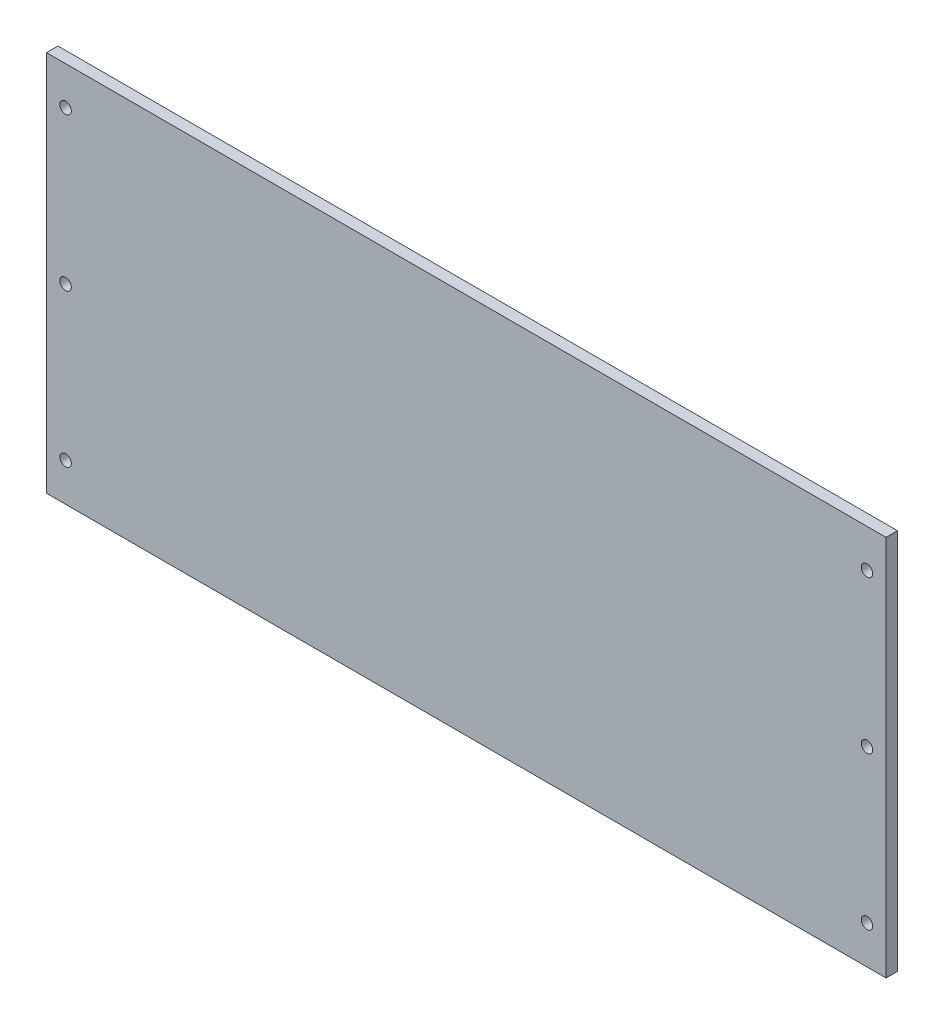
SolidWorks part; units mm, degrees
ref_plane "Plan de face" through (0, 0, 0) normal (0, 0, 1) x (1, 0, 0)
ref_plane "Plan de dessus" through (0, 0, 0) normal (0, 1, 0) x (1, 0, 0)
ref_plane "Plan de droite" through (0, 0, 0) normal (1, 0, 0) x (0, 0, -1)
sketch "Esquisse1" plane through (0, 0, 0) normal (0, 0, 1) x (1, 0, 0)
  line L0 (-105, -50) -> (-105, 50) construction
  line L1 (110, -50) -> (-110, -50)
  line L2 (110, -50) -> (110, 50)
  line L3 (110, 50) -> (-110, 50)
  line L4 (-110, -50) -> (-110, 50)
  line L5 (110, -50) -> (-110, 50) construction
  line L6 (110, 50) -> (-110, -50) construction
  line L7 (0, 50) -> (0, -50) construction
  circle A0 centre (-105, -40) radius 1.5
  circle A1 centre (-105, 0) radius 1.5
  circle A2 centre (-105, 40) radius 1.5
  circle A3 centre (105, 40) radius 1.5
  circle A4 centre (105, 0) radius 1.5
  circle A5 centre (105, -40) radius 1.5
  point P0 (0, 0)
  dimension "D4" = 3
  dimension "D1" = 220
  dimension "D2" = 100
  dimension "D3" = 5
  dimension "D5" = 10
  dimension "D7" = 10
  dimension "D6" = 3
extrude "Boss.-Extru.1" add sketch "Esquisse1" along normal blind 3
